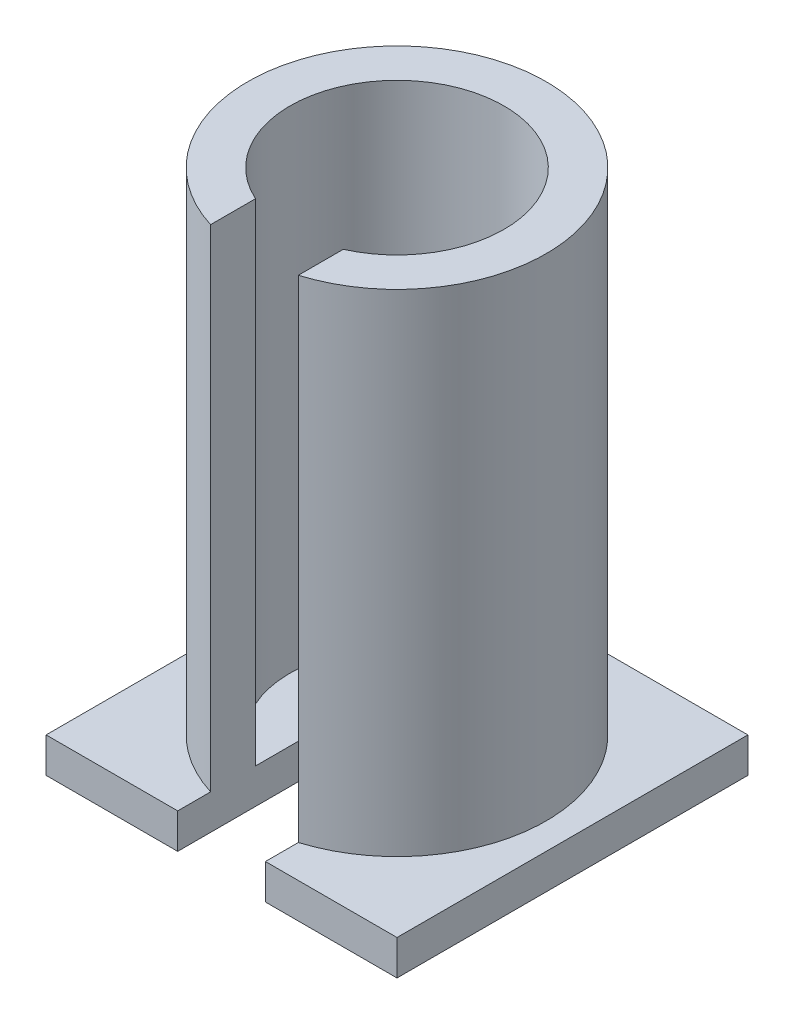
SolidWorks part; units mm, degrees
ref_plane "Front Plane" through (0, 0, 0) normal (0, 0, 1) x (1, 0, 0)
ref_plane "Top Plane" through (0, 0, 0) normal (0, 1, 0) x (1, 0, 0)
ref_plane "Right Plane" through (0, 0, 0) normal (1, 0, 0) x (0, 0, -1)
sketch "Sketch1" plane through (0, 0, 0) normal (0, 1, 0) x (1, 0, 0)
  line L0 (0, 0) -> (0, -4.25)
  circle A0 centre (0, 0) radius 4.25
  circle A1 centre (0, 0) radius 3.05
  dimension "D1" = 8.5
  dimension "D2" = 6.1
extrude "Boss-Extrude1" add sketch "Sketch1" along normal blind 15
sketch "Sketch2" plane through (0, 0, 0) normal (0, 1, 0) x (1, 0, 0)
  circle A0 centre (0, 0) radius 3.05
  circle A1 centre (0, 0) radius 1.25
  dimension "D1" = 6.1
  dimension "D2" = 2.5
extrude "Boss-Extrude2" add sketch "Sketch2" along normal blind 1
sketch "Sketch3" plane through (0, 0, 0) normal (0, 1, 0) x (1, 0, 0)
  line L0 (-1.25, 0) -> (1.25, 0)
  line L1 (-1.25, 0) -> (-1.25, -5.0723)
  line L2 (1.25, 0) -> (1.25, -5.0723)
  line L3 (-1.25, -5.0723) -> (1.25, -5.0723)
  circle A0 centre (0, 0) radius 1.25
extrude "Cut-Extrude1" cut sketch "Sketch3" along normal blind 15 contours A0 L1 L3 L2
sketch "Sketch4" plane through (0, 0, 0) normal (0, 1, 0) x (1, 0, 0)
  line L0 (-1.25, 0) -> (1.25, 0)
  line L1 (5, -5) -> (-5, -5)
  line L2 (5, -5) -> (5, 5)
  line L3 (5, 5) -> (-5, 5)
  line L4 (-5, -5) -> (-5, 5)
  line L5 (5, -5) -> (-5, 5) construction
  line L6 (5, 5) -> (-5, -5) construction
  line L7 (-1.25, 0) -> (-1.25, -6.498)
  line L8 (1.25, 0) -> (1.25, -6.498)
  line L9 (-1.25, -6.498) -> (1.25, -6.498)
  circle A0 centre (0, 0) radius 1.25
  point P0 (0, 0)
  dimension "D3" = 2.5
  dimension "D1" = 10
  dimension "D2" = 10
extrude "Boss-Extrude3" add sketch "Sketch4" along normal blind 1 contours A0 L8 L1 L2 L3 L4 L7
